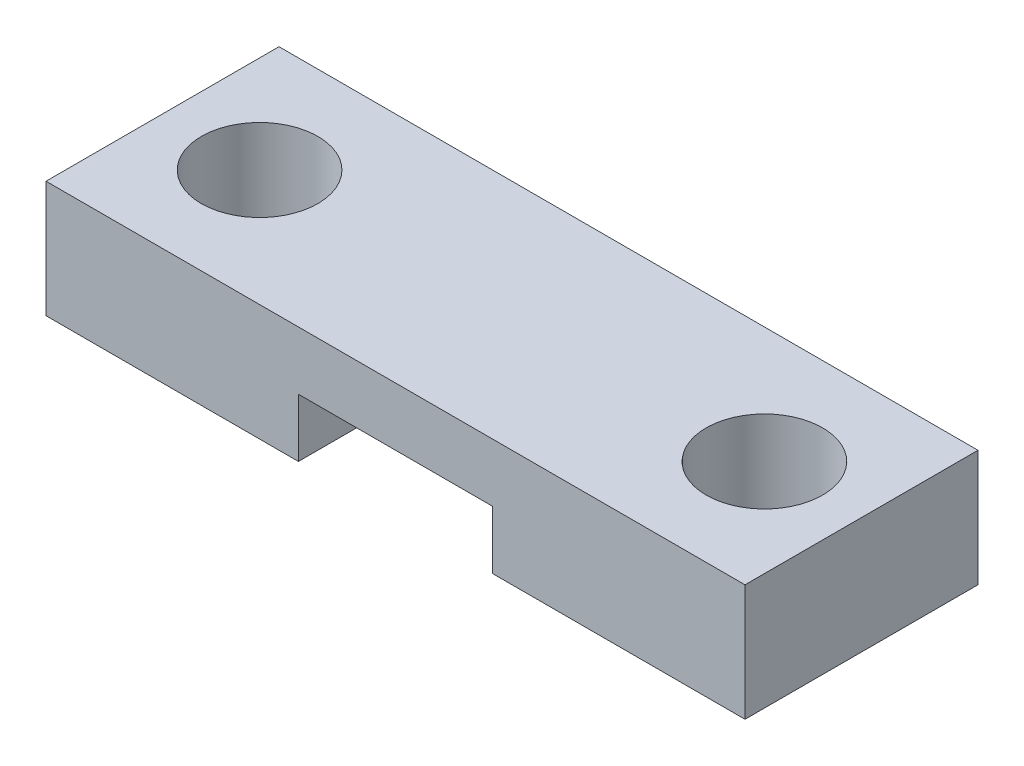
SolidWorks part; units mm, degrees
ref_plane "Front Plane" through (0, 0, 0) normal (0, 0, 1) x (1, 0, 0)
ref_plane "Top Plane" through (0, 0, 0) normal (0, 1, 0) x (1, 0, 0)
ref_plane "Right Plane" through (0, 0, 0) normal (1, 0, 0) x (0, 0, -1)
sketch "Sketch1" plane through (0, 0, 0) normal (0, 1, 0) x (1, 0, 0)
  line L1 (-9, -3) -> (9, -3)
  line L2 (-9, -3) -> (-9, 3)
  line L3 (-9, 3) -> (9, 3)
  line L4 (9, -3) -> (9, 3)
  line L5 (-9, -3) -> (9, 3) construction
  line L6 (-9, 3) -> (9, -3) construction
  circle A0 centre (-6.5, 0) radius 1.5
  circle A1 centre (6.5, 0) radius 1.5
  point P0 (0, 0)
  point P10 (9, 0)
  dimension "D3" = 3
  dimension "D1" = 18
  dimension "D2" = 6
  dimension "D4" = 2.5
  dimension "D5" = 2.5
extrude "Boss-Extrude1" add sketch "Sketch1" along normal blind 3
sketch "Sketch2" plane through (0, 0, 3) normal (0, 0, 1) x (1, 0, 0)
  line L0 (-9, 0) -> (9, 0) construction
  line L1 (-2.5, 0) -> (2.5, 0)
  line L2 (-2.5, 0) -> (-2.5, 1.5)
  line L3 (-2.5, 1.5) -> (2.5, 1.5)
  line L4 (2.5, 0) -> (2.5, 1.5)
  line L5 (-9, 3) -> (9, 3) construction
  point P8 (0, 3)
  point P9 (0, 1.5)
  dimension "D1" = 5
  dimension "D2" = 1.5
extrude "Cut-Extrude1" cut sketch "Sketch2" against normal through all
